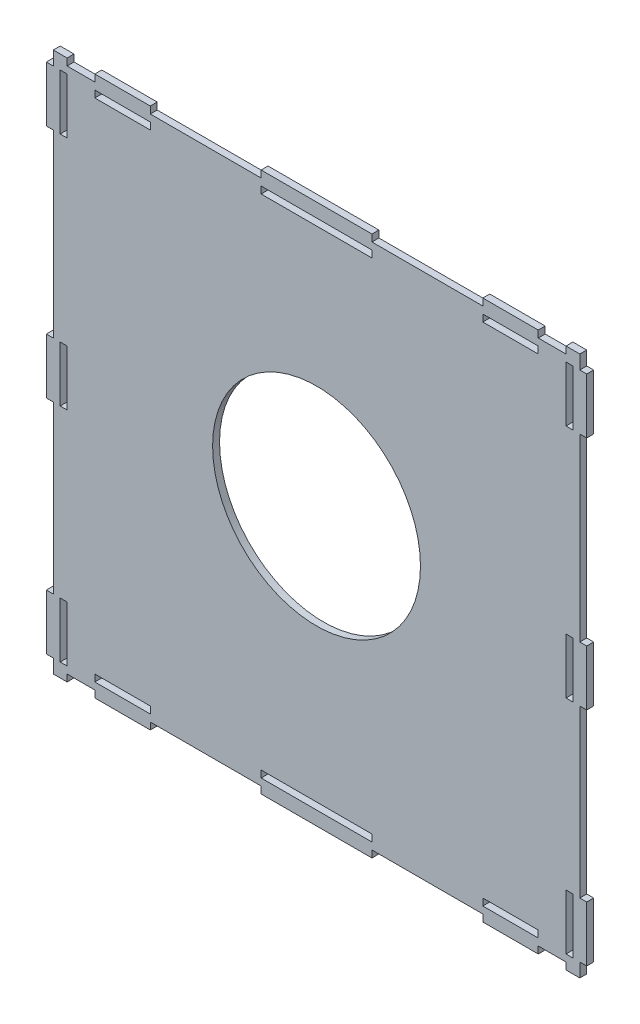
SolidWorks part; units mm, degrees
material "Plastique personnalisé"
ref_plane "Plan de face" through (0, 0, 0) normal (0, 0, 1) x (1, 0, 0)
ref_plane "Plan de dessus" through (0, 0, 0) normal (0, 1, 0) x (1, 0, 0)
ref_plane "Plan de droite" through (0, 0, 0) normal (1, 0, 0) x (0, 0, -1)
sketch "Esquisse1" plane through (0, 0, 0) normal (0, 0, 1) x (1, 0, 0)
  line L0 (-243.1425, -175.4403) -> (-233.1425, -175.4403) construction
  line L1 (-243.1425, -263.4066) -> (146.8575, -263.4066)
  line L2 (-243.1425, -263.4066) -> (-243.1425, 126.5934)
  line L3 (-243.1425, 126.5934) -> (146.8575, 126.5934)
  line L4 (146.8575, -263.4066) -> (146.8575, 126.5934)
  line L5 (-233.1425, -263.4066) -> (-233.1425, -253.4066) construction
  line L6 (-233.1425, 126.5934) -> (-233.1425, 116.5934) construction
  line L10 (136.8575, -253.4066) -> (136.8575, 116.5934)
  line L11 (136.8575, 116.5934) -> (-233.1425, 116.5934)
  line L12 (146.8575, -100.9201) -> (136.8575, -100.9201) construction
  line L13 (-228.1425, -253.4066) -> (-228.1425, -213.4066)
  line L14 (-228.1425, -213.4066) -> (-233.1425, -213.4066)
  line L16 (-233.1425, 116.5934) -> (-228.1425, 116.5934)
  line L17 (-228.1425, 116.5934) -> (-228.1425, 76.5934)
  line L18 (-228.1425, 76.5934) -> (-233.1425, 76.5934)
  line L19 (-233.1425, 76.5934) -> (-233.1425, 116.5934)
  line L21 (-233.1425, -253.4066) -> (-228.1425, -253.4066)
  line L22 (-233.1425, -253.4066) -> (-233.1425, -213.4066)
  line L23 (-233.1425, 76.5934) -> (-233.1425, -213.4066)
  line L24 (136.8575, -253.4066) -> (-233.1425, -253.4066)
  line L29 (136.8575, 76.5934) -> (136.8575, 116.5934)
  line L30 (131.8575, 76.5934) -> (136.8575, 76.5934)
  line L31 (131.8575, 116.5934) -> (131.8575, 76.5934)
  line L32 (136.8575, 116.5934) -> (131.8575, 116.5934)
  line L33 (136.8575, -253.4066) -> (131.8575, -253.4066)
  line L34 (131.8575, -253.4066) -> (131.8575, -213.4066)
  line L35 (131.8575, -213.4066) -> (136.8575, -213.4066)
  line L36 (136.8575, -253.4066) -> (136.8575, -213.4066)
  line L37 (-233.1425, -93.4066) -> (-233.1425, -53.4066)
  line L38 (-228.1425, -53.4066) -> (-233.1425, -53.4066)
  line L39 (-228.1425, -93.4066) -> (-228.1425, -53.4066)
  line L40 (-233.1425, -93.4066) -> (-228.1425, -93.4066)
  line L41 (136.8575, -93.4066) -> (131.8575, -93.4066)
  line L42 (131.8575, -93.4066) -> (131.8575, -53.4066)
  line L43 (131.8575, -53.4066) -> (136.8575, -53.4066)
  line L44 (136.8575, -93.4066) -> (136.8575, -53.4066)
  line L46 (-8.1425, 111.5934) -> (-8.1425, 116.5934)
  line L47 (-8.1425, 116.5934) -> (-48.1425, 116.5934)
  line L49 (-88.1425, 111.5934) -> (-88.1425, 116.5934)
  line L50 (-88.1425, 116.5934) -> (-48.1425, 116.5934)
  line L51 (-88.1425, -248.4066) -> (-48.1425, -248.4066)
  line L52 (-8.1425, -248.4066) -> (-48.1425, -248.4066)
  line L53 (-8.1425, -253.4066) -> (-8.1425, -248.4066)
  line L54 (-48.1425, -253.4066) -> (-8.1425, -253.4066)
  line L55 (-48.1425, -253.4066) -> (-88.1425, -253.4066)
  line L56 (-88.1425, -253.4066) -> (-88.1425, -248.4066)
  line L58 (71.8575, 116.5934) -> (71.8575, 111.5934)
  line L59 (71.8575, 111.5934) -> (111.8575, 111.5934)
  line L60 (111.8575, 111.5934) -> (111.8575, 116.5934)
  line L61 (111.8575, 116.5934) -> (71.8575, 116.5934)
  line L62 (71.8575, -248.4066) -> (71.8575, -253.4066)
  line L63 (71.8575, -253.4066) -> (111.8575, -253.4066)
  line L64 (111.8575, -253.4066) -> (111.8575, -248.4066)
  line L65 (111.8575, -248.4066) -> (71.8575, -248.4066)
  line L70 (111.8575, -263.4066) -> (71.8575, -263.4066)
  line L71 (71.8575, -263.4066) -> (71.8575, -258.4066)
  line L72 (-8.1425, -253.4066) -> (-8.1425, -248.4066) [skipped]
  line L73 (-8.1425, -248.4066) -> (-48.1425, -248.4066) [skipped]
  line L74 (-88.1425, 111.5934) -> (-48.1425, 111.5934)
  line L76 (-168.1425, 116.5934) -> (-168.1425, 111.5934)
  line L77 (-208.1425, 111.5934) -> (-168.1425, 111.5934)
  line L78 (-208.1425, 111.5934) -> (-208.1425, 116.5934)
  line L79 (-208.1425, 116.5934) -> (-168.1425, 116.5934)
  line L80 (-168.1425, -248.4066) -> (-168.1425, -253.4066)
  line L81 (-208.1425, -253.4066) -> (-168.1425, -253.4066)
  line L82 (-208.1425, -253.4066) -> (-208.1425, -248.4066)
  line L83 (-208.1425, -248.4066) -> (-168.1425, -248.4066)
  line L88 (71.8575, -258.4066) -> (-8.1425, -258.4066)
  line L89 (-88.1425, -253.4066) -> (-48.1425, -253.4066) [skipped]
  line L90 (-88.1425, -253.4066) -> (-88.1425, -248.4066) [skipped]
  line L91 (-88.1425, -248.4066) -> (-48.1425, -248.4066) [skipped]
  line L92 (-48.1425, 111.5934) -> (-8.1425, 111.5934)
  line L93 (-8.1425, -258.4066) -> (-8.1425, -263.4066)
  line L94 (111.8575, -263.4066) -> (111.8575, -258.4066)
  line L95 (111.8575, -258.4066) -> (131.8575, -258.4066)
  line L96 (131.8575, -258.4066) -> (131.8575, -263.4066)
  line L97 (131.8575, -263.4066) -> (146.8575, -263.4066)
  line L98 (-8.1425, -263.4066) -> (-88.1425, -263.4066)
  line L99 (-88.1425, -263.4066) -> (-88.1425, -258.4066)
  line L100 (-88.1425, -258.4066) -> (-168.1425, -258.4066)
  line L101 (-168.1425, -258.4066) -> (-168.1425, -263.4066)
  line L102 (-168.1425, -263.4066) -> (-208.1425, -263.4066)
  line L103 (-208.1425, -263.4066) -> (-208.1425, -258.4066)
  line L104 (-208.1425, -258.4066) -> (-228.1425, -258.4066)
  line L105 (-228.1425, -258.4066) -> (-228.1425, -263.4066)
  line L106 (-228.1425, -263.4066) -> (-238.1425, -263.4066)
  line L107 (131.8575, -263.4066) -> (141.8575, -263.4066)
  line L108 (-238.1425, -263.4066) -> (-238.1425, -253.4066)
  line L109 (-238.1425, -253.4066) -> (-243.1425, -253.4066)
  line L110 (141.8575, -263.4066) -> (141.8575, -253.4066)
  line L111 (141.8575, -253.4066) -> (146.8575, -253.4066)
  line L112 (146.8575, -253.4066) -> (146.8575, -213.4066)
  line L113 (146.8575, -213.4066) -> (141.8575, -213.4066)
  line L114 (141.8575, -213.4066) -> (141.8575, -93.4066)
  line L115 (141.8575, -93.4066) -> (146.8575, -93.4066)
  line L116 (146.8575, -93.4066) -> (146.8575, -53.4066)
  line L117 (146.8575, -53.4066) -> (141.8575, -53.4066)
  line L118 (141.8575, -53.4066) -> (141.8575, 76.5934)
  line L119 (141.8575, 76.5934) -> (146.8575, 76.5934)
  line L120 (146.8575, 76.5934) -> (146.8575, 116.5934)
  line L121 (146.8575, 116.5934) -> (141.8575, 116.5934)
  line L122 (-243.1425, -253.4066) -> (-243.1425, -213.4066)
  line L123 (-243.1425, -213.4066) -> (-238.1425, -213.4066)
  line L124 (-238.1425, -213.4066) -> (-238.1425, -93.4066)
  line L125 (-238.1425, -93.4066) -> (-243.1425, -93.4066)
  line L126 (-243.1425, -93.4066) -> (-243.1425, -53.4066)
  line L127 (-243.1425, -53.4066) -> (-238.1425, -53.4066)
  line L128 (-238.1425, -53.4066) -> (-238.1425, 76.5934)
  line L129 (-238.1425, 76.5934) -> (-243.1425, 76.5934)
  line L130 (-243.1425, 76.5934) -> (-243.1425, 116.5934)
  line L131 (-243.1425, 116.5934) -> (-238.1425, 116.5934)
  line L132 (-238.1425, 116.5934) -> (-238.1425, 126.5934)
  line L133 (-238.1425, 126.5934) -> (-228.1425, 126.5934)
  line L134 (-228.1425, 126.5934) -> (-228.1425, 121.5934)
  line L135 (-228.1425, 121.5934) -> (-208.1425, 121.5934)
  line L136 (-208.1425, 121.5934) -> (-208.1425, 126.5934)
  line L137 (-208.1425, 126.5934) -> (-168.1425, 126.5934)
  line L138 (-168.1425, 126.5934) -> (-168.1425, 121.5934)
  line L139 (-168.1425, 121.5934) -> (-88.1425, 121.5934)
  line L140 (-88.1425, 121.5934) -> (-88.1425, 126.5934)
  line L141 (-88.1425, 126.5934) -> (-8.1425, 126.5934)
  line L142 (-8.1425, 126.5934) -> (-8.1425, 121.5934)
  line L143 (-8.1425, 121.5934) -> (71.8575, 121.5934)
  line L144 (71.8575, 121.5934) -> (71.8575, 126.5934)
  line L145 (71.8575, 126.5934) -> (111.8575, 126.5934)
  line L146 (111.8575, 126.5934) -> (111.8575, 121.5934)
  line L147 (111.8575, 121.5934) -> (131.8575, 121.5934)
  line L148 (131.8575, 121.5934) -> (131.8575, 126.5934)
  line L149 (131.8575, 126.5934) -> (141.8575, 126.5934)
  line L150 (141.8575, 126.5934) -> (141.8575, 116.5934)
  circle A0 centre (-48.1425, -63.4066) radius 75
  dimension "D3" = 10
  dimension "D19" = 150
  dimension "D1" = 390
  dimension "D2" = 390
  dimension "D4" = 5
  dimension "D5" = 10
  dimension "D6" = 5
  dimension "D7" = 2
  dimension "D8" = 2
  dimension "D9" = 40
  dimension "D10" = 40
  dimension "D11" = 5
  dimension "D12" = 40
  dimension "D13" = 40
  dimension "D20" = 10
  dimension "D21" = 10
  dimension "D22" = 10
  dimension "D23" = 10
  dimension "D24" = 5
  dimension "D25" = 40
  dimension "D26" = 10
  dimension "D27" = 10
  dimension "D28" = 10
  dimension "D29" = 10
  dimension "D30" = 10
  dimension "D31" = 20
  dimension "D32" = 40
  dimension "D33" = 80
  dimension "D34" = 80
  dimension "D35" = 80
  dimension "D36" = 40
  dimension "D37" = 20
  dimension "D38" = 10
  dimension "D39" = 10
  dimension "D40" = 10
  dimension "D14" = 2
  dimension "D15" = 2
  dimension "D16" = 2
  dimension "D17" = 2
  dimension "D18" = 2
extrude "Boss.-Extru.1" add sketch "Esquisse1" along normal blind 5 contours L42 L43 L10 L30 L31 L11 L17 L18 L23 L38 L39 L40 L14 L13 L24 L34 L35 L41 | L1 L4 L3 L2 L10 L24 L21 L22 L23 L19 L11
